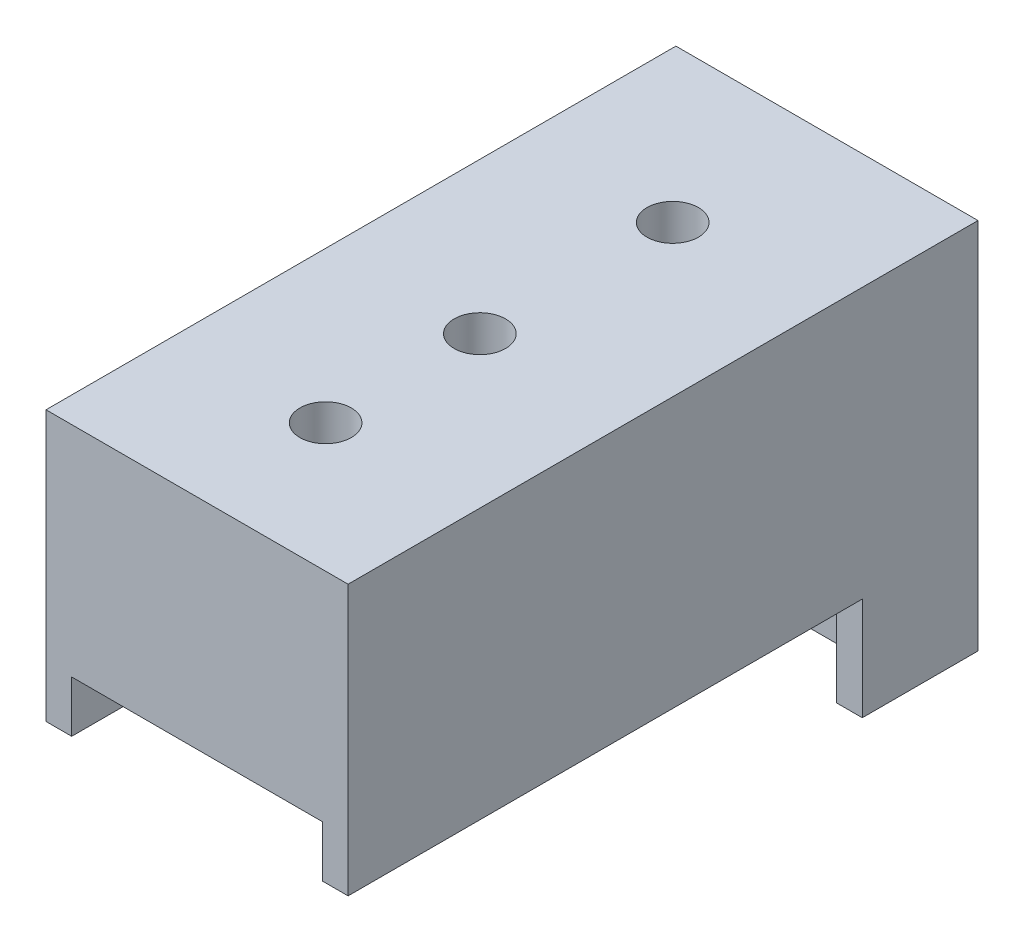
SolidWorks part; units mm, degrees
ref_plane "Front Plane" through (0, 0, 0) normal (0, 0, 1) x (1, 0, 0)
ref_plane "Top Plane" through (0, 0, 0) normal (0, 1, 0) x (1, 0, 0)
ref_plane "Right Plane" through (0, 0, 0) normal (1, 0, 0) x (0, 0, -1)
sketch "Sketch2" plane through (0, 0, 0) normal (1, 0, 0) x (0, 0, -1)
  line L0 (-44, 0) -> (0, 0)
  line L1 (0, 0) -> (0, -12)
  line L2 (-44, 0) -> (-44, 17)
  line L3 (-44, 17) -> (5, 17)
  line L4 (5, 17) -> (5, -12)
  line L5 (5, -12) -> (0, -12)
  dimension "D1" = 12
  dimension "D2" = 44
  dimension "D3" = 5
  dimension "D4" = 17
extrude "Boss-Extrude1" add sketch "Sketch2" along normal mid plane 19.5
sketch "Sketch3" plane through (9.75, 0, 0) normal (1, 0, 0) x (0, 0, -1)
  line L0 (-44, 17) -> (-44, -4)
  line L1 (-44, -4) -> (-4, -4)
  line L2 (-4, -4) -> (-4, -12)
  line L3 (-4, -12) -> (5, -12)
  line L6 (-44, 17) -> (5, 17)
  line L7 (5, 17) -> (5, -12)
  line L8 (0, 0) -> (0, -12) construction
  line L9 (-44, 0) -> (0, 0) construction
  dimension "D1" = 4
  dimension "D2" = 4
extrude "Boss-Extrude2" add sketch "Sketch3" along normal blind 2
mirror "Mirror1" about plane through (0, 0, 0) normal (1, 0, 0) of "Boss-Extrude2"
sketch "Sketch4" plane through (0, 0, 0) normal (0, -1, 0) x (1, 0, 0)
  line L0 (0, 0) -> (0, 7) construction
  line L1 (9.75, 0) -> (-9.75, 0) construction
  line L2 (0, 7) -> (0, 22) construction
  line L3 (0, 22) -> (0, 34) construction
  circle A0 centre (0, 34) radius 2
  circle A1 centre (0, 22) radius 2
  circle A2 centre (0, 7) radius 2
  dimension "D1" = 4
  dimension "D2" = 7
  dimension "D3" = 15
  dimension "D4" = 12
extrude "Cut-Extrude1" cut sketch "Sketch4" against normal through all
sketch "Sketch5" plane through (0, 0, 0) normal (0, 0, 1) x (1, 0, 0)
  line L0 (0, -7) -> (0, -12) construction
  line L1 (9.75, -12) -> (-9.75, -12) construction
  circle A0 centre (0, -7) radius 1.75
  dimension "D1" = 3.5
  dimension "D2" = 5
extrude "Cut-Extrude2" cut sketch "Sketch5" against normal through all
